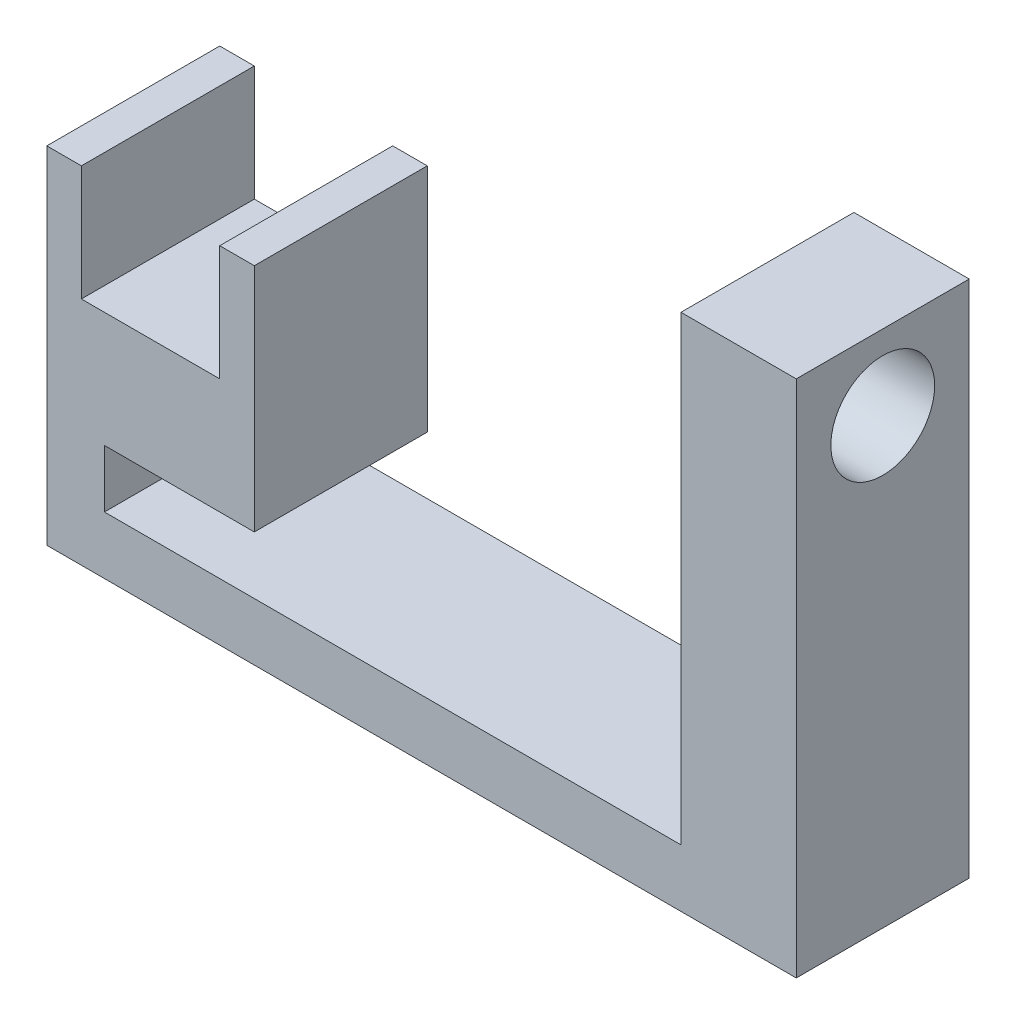
SolidWorks part; units mm, degrees
ref_plane "Спереди" through (0, 0, 0) normal (0, 0, 1) x (1, 0, 0)
ref_plane "Сверху" through (0, 0, 0) normal (0, 1, 0) x (1, 0, 0)
ref_plane "Справа" through (0, 0, 0) normal (1, 0, 0) x (0, 0, -1)
sketch "Эскиз4" plane through (0, 0, 0) normal (0, 0, 1) x (1, 0, 0)
  line L0 (0, 0) -> (0, -20)
  line L1 (0, -20) -> (0, -30)
  line L2 (0, 0) -> (3, 0)
  line L3 (3, 0) -> (3, -10)
  line L4 (3, -10) -> (15, -10)
  line L5 (15, -10) -> (15, 0)
  line L6 (15, 0) -> (18, 0)
  line L7 (18, 0) -> (18, -20)
  line L8 (18, -20) -> (5, -20)
  line L9 (5, -20) -> (5, -25)
  line L10 (0, -30) -> (65, -30)
  line L11 (5, -25) -> (55, -25)
  line L12 (55, -25) -> (55, 15)
  line L13 (55, 15) -> (65, 15)
  line L14 (65, 15) -> (65, -30)
  dimension "D1" = 20
  dimension "D2" = 10
  dimension "D3" = 3
  dimension "D4" = 10
  dimension "D5" = 12
  dimension "D6" = 10
  dimension "D7" = 3
  dimension "D8" = 13
  dimension "D9" = 20
  dimension "D10" = 5
  dimension "D11" = 65
  dimension "D12" = 50
  dimension "D13" = 40
  dimension "D14" = 10
extrude "Бобышка-Вытянуть1" add sketch "Эскиз4" along normal blind 15
sketch "Эскиз5" plane through (65, 0, 0) normal (1, 0, 0) x (0, 0, -1)
  line L0 (0, -30) -> (0, 15) construction
  line L1 (-15, -30) -> (0, -30) construction
  circle A0 centre (-7.5, 8.5) radius 4.5
  dimension "D1" = 9
  dimension "D2" = 7.5
  dimension "D3" = 38.5
extrude "Вырез-Вытянуть1" cut sketch "Эскиз5" against normal blind 15
